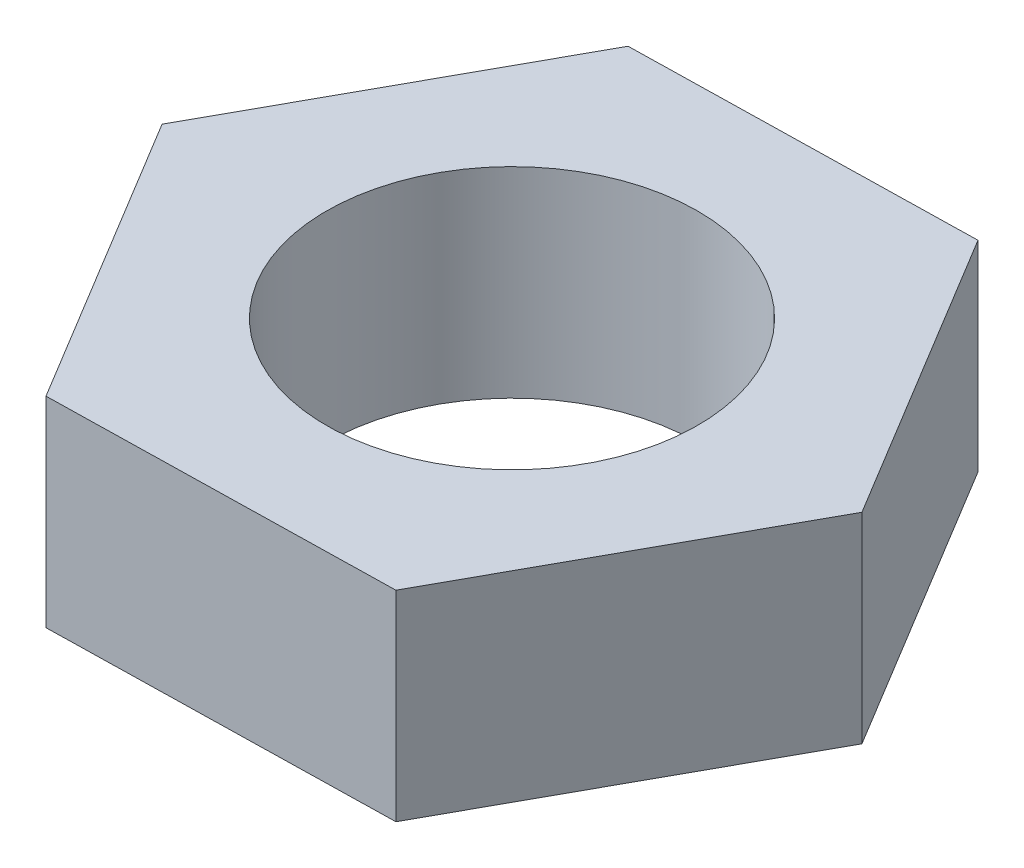
SolidWorks part; units mm, degrees
ref_plane "前视基准面" through (0, 0, 0) normal (0, 0, 1) x (1, 0, 0)
ref_plane "上视基准面" through (0, 0, 0) normal (0, 1, 0) x (1, 0, 0)
ref_plane "右视基准面" through (0, 0, 0) normal (1, 0, 0) x (0, 0, -1)
sketch "Sketch1" plane through (0, 0, 0) normal (0, 1, 0) x (1, 0, 0)
  line L1 (2.3899, -3.9525) -> (4.6179, 0.0934)
  line L2 (4.6179, 0.0934) -> (2.228, 4.0459)
  line L3 (2.228, 4.0459) -> (-2.3899, 3.9525)
  line L4 (-2.3899, 3.9525) -> (-4.6179, -0.0934)
  line L5 (-4.6179, -0.0934) -> (-2.228, -4.0459)
  line L6 (-2.228, -4.0459) -> (2.3899, -3.9525)
  circle A0 centre (0, 0) radius 4 construction
  circle A1 centre (0, 0) radius 2.5
extrude "Boss-Extrude1" add sketch "Sketch1" along normal blind 2.7
